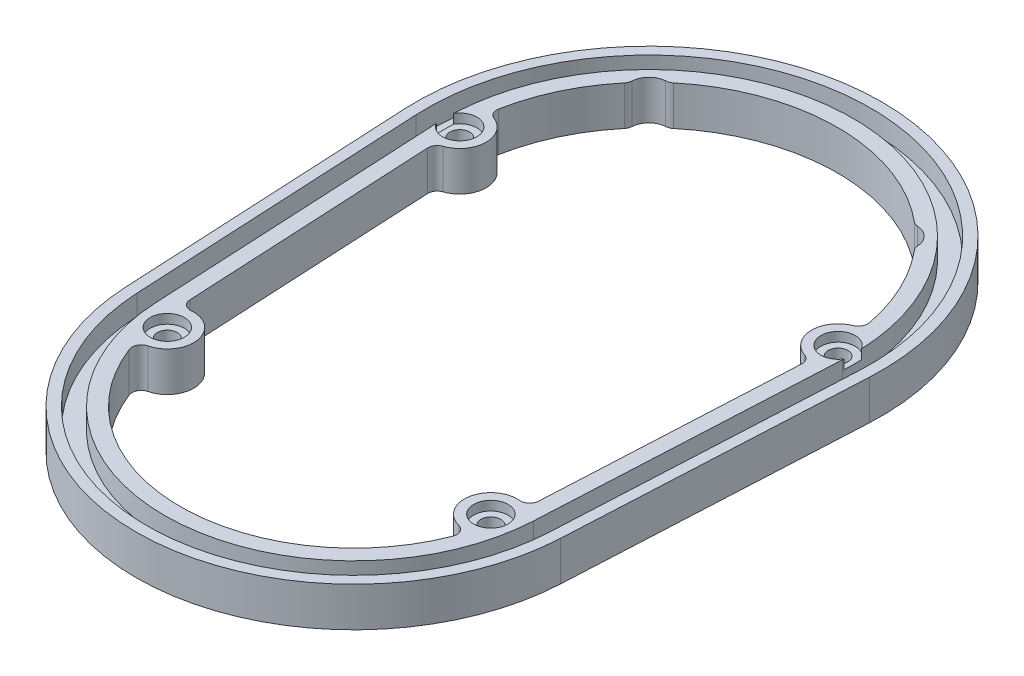
SolidWorks part; units mm, degrees
material "PC High Viscosity"
ref_plane "Front Plane" through (0, 0, 0) normal (0, 0, 1) x (1, 0, 0)
ref_plane "Top Plane" through (0, 0, 0) normal (0, 1, 0) x (1, 0, 0)
ref_plane "Right Plane" through (0, 0, 0) normal (1, 0, 0) x (0, 0, -1)
sketch "Sketch1" plane through (0, 0, 0) normal (0, 1, 0) x (1, 0, 0)
  line L0 (0, 0) -> (0, 102.8) construction
  line L1 (0, 0) -> (0, -40) construction
  line L2 (0, -40) -> (0, -52) construction
  line L3 (-74.7041, 99.0127) -> (-69.9102, 4.4557)
  line L4 (74.7041, 99.0127) -> (69.9102, 4.4557)
  line L5 (0, 102.8) -> (0, 165.6) construction
  line L6 (0, 102.8) -> (44.4063, 147.2063) construction
  line L7 (0, 102.8) -> (62.8, 102.8) construction
  line L8 (35.921, 138.721) -> (44.4063, 147.2063) construction
  line L10 (0, 102.8) -> (-74.8, 102.8) construction
  line L11 (0, 102.8) -> (0, 177.6) construction
  line L12 (0, 177.6) -> (-74.8, 177.6) construction
  line L13 (-74.8, 102.8) -> (-74.8, 177.6) construction
  line L14 (0, 0) -> (-74.8, 0) construction
  line L15 (0, 0) -> (0, -62) construction
  line L16 (0, -62) -> (-74.8, -62) construction
  line L17 (-74.8, 0) -> (-74.8, -62) construction
  circle A0 centre (0, 0) radius 40
  circle A1 centre (0, 102.8) radius 50.8
  circle A2 centre (0, 102.8) radius 62.8 construction
  circle A3 centre (0, 102.8) radius 74.8 construction
  circle A4 centre (0, 8) radius 60 construction
  circle A5 centre (0, 8) radius 70 construction
  arc A6 (-74.7041, 99.0127) -> (74.7041, 99.0127) centre (0, 102.8) cw
  arc A7 (-69.9102, 4.4557) -> (69.9102, 4.4557) centre (0, 8) ccw
  circle A8 centre (40.1637, 142.9637) radius 5.75
  circle A9 centre (40.1637, 62.6363) radius 5.75
  circle A10 centre (-40.1637, 62.6363) radius 5.75
  circle A11 centre (-40.1637, 142.9637) radius 5.75
  circle A12 centre (0, 102.8) radius 56.8 construction
  point P32 (0, 102.8)
  dimension "D1" = 80
  dimension "D2" = 101.6
  dimension "D4" = 12
  dimension "D3" = 12
  dimension "D5" = 10
  dimension "D6" = 120
  dimension "D7" = 12
  dimension "D9" = 11.5
  dimension "D8" = 45
  dimension "D11" = 239.6
  dimension "D12" = 149.6
  dimension "D10" = 4
extrude "Boss-Extrude1" add sketch "Sketch1" along normal blind 12.7
sketch "Sketch10" plane through (0, 12.7, 0) normal (0, 1, 0) x (1, 0, 0)
  line L0 (0, 0) -> (-52, 0) construction
  line L1 (0, 102.8) -> (-60.8, 102.8) construction
  line L2 (0, 102.8) -> (0, 0) construction
  circle A0 centre (0, 0) radius 52 construction
  circle A1 centre (0, 0) radius 40 construction
  circle A2 centre (-52, 0) radius 3.175
  circle A3 centre (0, 102.8) radius 60.8 construction
  circle A4 centre (0, 102.8) radius 50.8 construction
  circle A5 centre (-60.8, 102.8) radius 3.175
  circle A6 centre (60.8, 102.8) radius 3.175
  circle A7 centre (52, 0) radius 3.175
  dimension "D1" = 12
  dimension "D2" = 6.35
  dimension "D3" = 10
  dimension "D4" = 6.35
  dimension "D5" = 121.6
extrude "Cut-Extrude6" cut sketch "Sketch10" against normal through all
sketch "Sketch12" plane through (0, 12.7, 0) normal (0, 1, 0) x (1, 0, 0)
  circle A0 centre (-60.8, 102.8) radius 5.5
  circle A1 centre (60.8, 102.8) radius 5.5
  circle A2 centre (52, 0) radius 5.5
  circle A3 centre (-52, 0) radius 5.5
  dimension "D1" = 11
extrude "Cut-Extrude8" cut sketch "Sketch12" against normal blind 3
sketch "Sketch13" plane through (0, 12.7, 0) normal (0, 1, 0) x (1, 0, 0)
  line L0 (-71.2085, 99.1899) -> (-66.4147, 4.6329)
  line L1 (66.4147, 4.6329) -> (71.2085, 99.1899)
  line L2 (-74.7041, 99.0127) -> (-69.9102, 4.4557)
  line L3 (69.9102, 4.4557) -> (74.7041, 99.0127)
  line L4 (-74.7041, 99.0127) -> (-69.9102, 4.4557) construction
  line L5 (69.9102, 4.4557) -> (74.7041, 99.0127) construction
  line L6 (-65.5159, 99.4785) -> (-60.722, 4.9215)
  line L7 (60.722, 4.9215) -> (65.5159, 99.4785)
  arc A0 (71.2085, 99.1899) -> (-71.2085, 99.1899) centre (0, 102.8) ccw
  arc A1 (-66.4147, 4.6329) -> (66.4147, 4.6329) centre (0, 8) ccw
  arc A2 (74.7041, 99.0127) -> (-74.7041, 99.0127) centre (0, 102.8) ccw
  arc A3 (-69.9102, 4.4557) -> (69.9102, 4.4557) centre (0, 8) ccw
  arc A4 (74.7041, 99.0127) -> (-74.7041, 99.0127) centre (0, 102.8) ccw construction
  arc A5 (-69.9102, 4.4557) -> (69.9102, 4.4557) centre (0, 8) ccw construction
  arc A6 (-60.722, 4.9215) -> (60.722, 4.9215) centre (0, 8) ccw
  arc A7 (65.5159, 99.4785) -> (-65.5159, 99.4785) centre (0, 102.8) ccw
  dimension "D1" = 0
  dimension "D2" = 3.5
  dimension "D3" = 5.7
extrude "Cut-Extrude9" cut sketch "Sketch13" against normal blind 6.5
sketch "Sketch14" plane through (0, 12.7, 0) normal (0, 1, 0) x (1, 0, 0)
  line L0 (0, 102.8) -> (0, 0) construction
  line L1 (-55.7284, 5.1747) -> (-60.5223, 99.7316) construction
  line L2 (-60.2478, 94.318) -> (-55.8503, 7.578)
  line L3 (0, 102.8) -> (0, 163.4) construction
  line L4 (0, 0) -> (0, -47.8) construction
  line L5 (60.2478, 94.318) -> (55.8503, 7.578)
  circle A0 centre (0, 102.8) radius 60.6 construction
  arc A1 (65.5159, 99.4785) -> (-65.5159, 99.4785) centre (0, 102.8) ccw construction
  arc A2 (-60.2478, 94.318) -> (-60.0062, 111.2629) centre (-60.8, 102.8) ccw
  circle A3 centre (-60.8, 102.8) radius 5.5 construction
  arc A4 (-53.3373, -8.3941) -> (-55.8503, 7.578) centre (-52, 0) ccw
  circle A5 centre (-52, 0) radius 5.5 construction
  circle A6 centre (0, 8) radius 55.8 construction
  arc A7 (-60.722, 4.9215) -> (60.722, 4.9215) centre (0, 8) ccw construction
  arc A8 (-60.0062, 111.2629) -> (0, 163.4) centre (0, 102.8) cw
  arc A9 (-53.3373, -8.3941) -> (0, -47.8) centre (0, 8) ccw
  arc A10 (53.3373, -8.3941) -> (0, -47.8) centre (0, 8) cw
  arc A11 (53.3373, -8.3941) -> (55.8503, 7.578) centre (52, 0) cw
  arc A12 (60.2478, 94.318) -> (60.0062, 111.2629) centre (60.8, 102.8) cw
  arc A13 (60.0062, 111.2629) -> (0, 163.4) centre (0, 102.8) ccw
  dimension "D1" = 5
  dimension "D2" = 3
  dimension "D3" = 3
  dimension "D4" = 5
extrude "Cut-Extrude10" cut sketch "Sketch14" against normal through all
fillet "Fillet1" radius 3 8 edges at (-60.0062, 6.35, -111.2629) (-53.3373, 6.35, 8.3941) (-55.8503, 6.35, -7.578) (-60.2478, 6.35, -94.318) (60.0062, 6.35, -111.2629) (60.2478, 6.35, -94.318) (55.8503, 6.35, -7.578) (53.3373, 6.35, 8.3941)
fillet "Fillet2" radius 3 4 edges at (-39.585, 6.35, -148.6845) (-45.8845, 6.35, -142.385) (39.585, 6.35, -148.6845) (45.8845, 6.35, -142.385)
